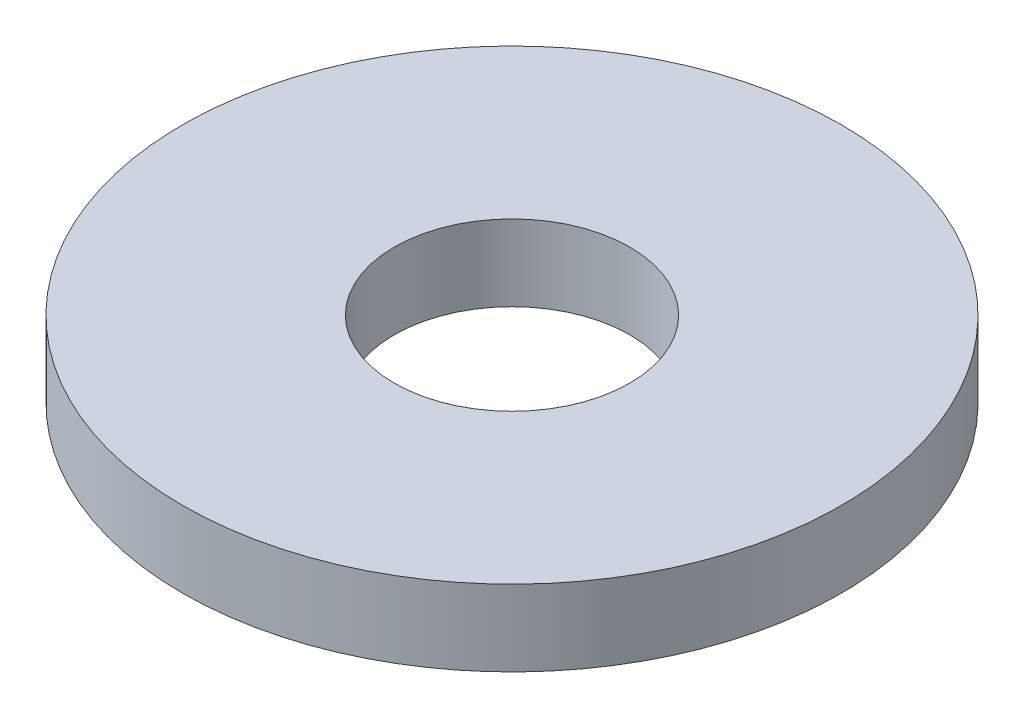
SolidWorks part; units mm, degrees
ref_plane "Front Plane" through (0, 0, 0) normal (0, 0, 1) x (1, 0, 0)
ref_plane "Top Plane" through (0, 0, 0) normal (0, 1, 0) x (1, 0, 0)
ref_plane "Right Plane" through (0, 0, 0) normal (1, 0, 0) x (0, 0, -1)
sketch "Sketch1" plane through (0, 0, 0) normal (0, 1, 0) x (1, 0, 0)
  circle A0 centre (0, 0) radius 11.0109
  circle A1 centre (0, 0) radius 3.937
  dimension "D1" = 22.0218
  dimension "D2" = 7.874
extrude "Boss-Extrude1" add sketch "Sketch1" along normal blind 2.54
